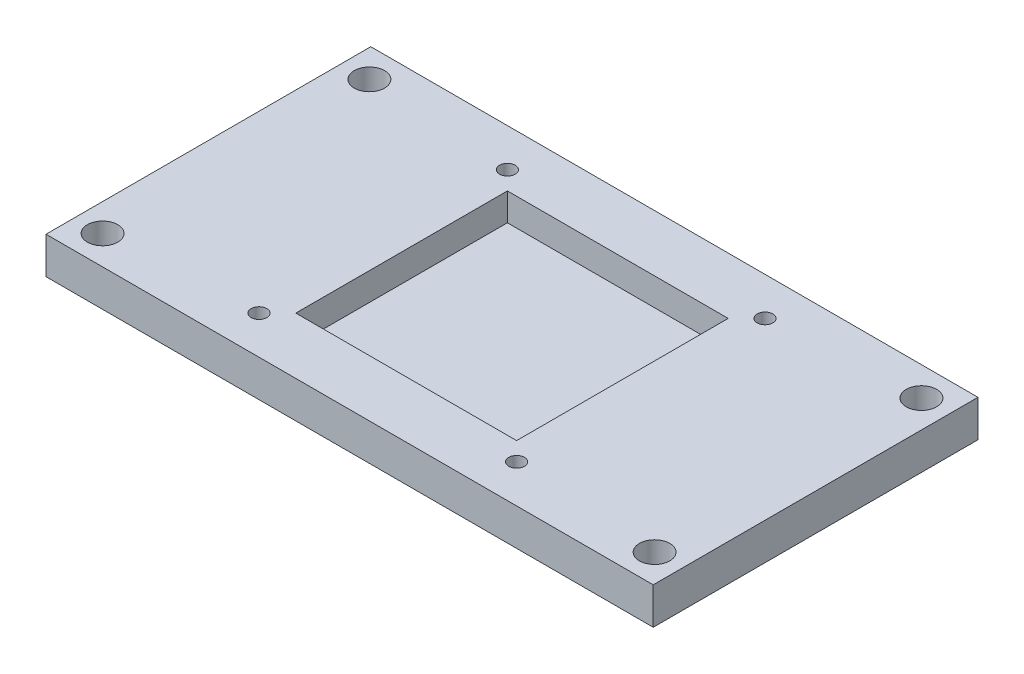
SolidWorks part; units mm, degrees
ref_plane "Front Plane" through (0, 0, 0) normal (0, 0, 1) x (1, 0, 0)
ref_plane "Top Plane" through (0, 0, 0) normal (0, 1, 0) x (1, 0, 0)
ref_plane "Right Plane" through (0, 0, 0) normal (1, 0, 0) x (0, 0, -1)
sketch "Sketch1" plane through (0, 0, 0) normal (0, 1, 0) x (1, 0, 0)
  line L0 (33, 35.3) -> (33, 0) construction
  line L1 (0, 0) -> (66, 0)
  line L2 (0, 0) -> (0, 35.3)
  line L3 (0, 35.3) -> (66, 35.3)
  line L4 (66, 0) -> (66, 35.3)
  line L5 (3, 3.15) -> (63, 3.15) construction
  line L6 (3, 3.15) -> (3, 32.15) construction
  line L7 (3, 32.15) -> (63, 32.15) construction
  line L8 (63, 3.15) -> (63, 32.15) construction
  line L9 (3, 3.15) -> (63, 32.15) construction
  line L10 (3, 32.15) -> (63, 3.15) construction
  circle A0 centre (3, 32.15) radius 1.65
  circle A1 centre (3, 3.15) radius 1.65
  circle A2 centre (63, 3.15) radius 1.65
  circle A3 centre (63, 32.15) radius 1.65
  point P5 (33, 17.65)
  dimension "D5" = 3.3
  dimension "D1" = 66
  dimension "D2" = 35.3
  dimension "D3" = 60
  dimension "D4" = 29
extrude "Boss-Extrude1" add sketch "Sketch1" along normal blind 4
sketch "Sketch2" plane through (0, 4, 0) normal (0, 1, 0) x (1, 0, 0)
  line L0 (33, 35.3) -> (33, 0) construction
  line L1 (66, 35.3) -> (0, 35.3) construction
  line L2 (0, 0) -> (66, 0) construction
  line L4 (19, 31.15) -> (47, 31.15) construction
  line L5 (19, 31.15) -> (19, 4.15) construction
  line L6 (19, 4.15) -> (47, 4.15) construction
  line L7 (47, 31.15) -> (47, 4.15) construction
  line L8 (19, 31.15) -> (47, 4.15) construction
  line L9 (19, 4.15) -> (47, 31.15) construction
  circle A0 centre (19, 31.15) radius 0.85
  circle A1 centre (19, 4.15) radius 0.85
  circle A2 centre (47, 4.15) radius 0.85
  circle A3 centre (47, 31.15) radius 0.85
  point P6 (33, 17.65)
  dimension "D3" = 1.7
  dimension "D1" = 27
  dimension "D2" = 28
extrude "Cut-Extrude1" cut sketch "Sketch2" against normal blind 4 contours A0 | A3 | A2 | A1
sketch "Sketch3" plane through (0, 4, 0) normal (0, 1, 0) x (1, 0, 0)
  line L0 (21, 29.15) -> (45, 29.15)
  line L1 (19, 31.15) -> (47, 31.15) construction
  line L2 (19, 31.15) -> (19, 4.15) construction
  line L3 (19, 4.15) -> (47, 4.15) construction
  line L4 (47, 31.15) -> (47, 4.15) construction
  line L5 (45, 29.15) -> (45, 6.15)
  line L6 (21, 6.15) -> (45, 6.15)
  line L7 (21, 29.15) -> (21, 6.15)
  dimension "D1" = 2
extrude "Cut-Extrude2" cut sketch "Sketch3" against normal blind 3
